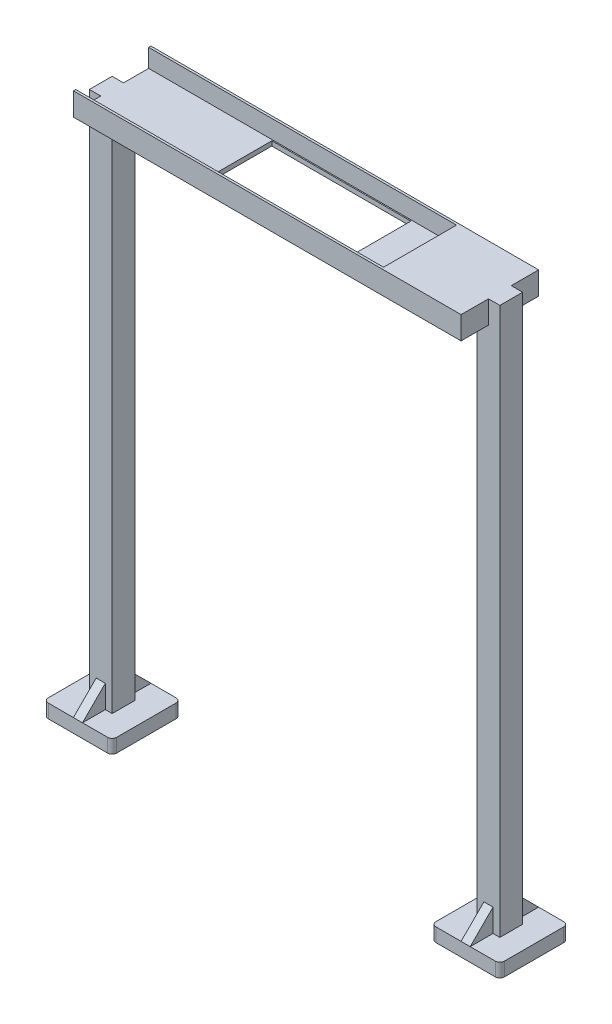
SolidWorks part; units mm, degrees
material "ABS"
ref_plane "Alzado" through (0, 0, 0) normal (0, 0, 1) x (1, 0, 0)
ref_plane "Planta" through (0, 0, 0) normal (0, 1, 0) x (1, 0, 0)
ref_plane "Vista lateral" through (0, 0, 0) normal (1, 0, 0) x (0, 0, -1)
sketch "Croquis1" plane through (0, 0, 0) normal (0, 1, 0) x (1, 0, 0)
  line L0 (42.5, 6.5) -> (42.5, -6.5) construction
  line L1 (-6.5, -7.5) -> (6.5, -7.5)
  line L2 (-7.5, -6.5) -> (-7.5, 6.5)
  line L3 (-6.5, 7.5) -> (6.5, 7.5)
  line L4 (7.5, -6.5) -> (7.5, 6.5)
  line L5 (-7.5, -7.5) -> (7.5, 7.5) construction
  line L6 (-7.5, 7.5) -> (7.5, -7.5) construction
  line L7 (92.5, 7.5) -> (77.5, -7.5) construction
  line L8 (92.5, -7.5) -> (77.5, 7.5) construction
  line L9 (77.5, -6.5) -> (77.5, 6.5)
  line L10 (91.5, 7.5) -> (78.5, 7.5)
  line L11 (92.5, -6.5) -> (92.5, 6.5)
  line L12 (91.5, -7.5) -> (78.5, -7.5)
  arc A0 (6.5, -7.5) -> (7.5, -6.5) centre (6.5, -6.5) ccw
  arc A1 (6.5, 7.5) -> (7.5, 6.5) centre (6.5, 6.5) cw
  arc A2 (-7.5, 6.5) -> (-6.5, 7.5) centre (-6.5, 6.5) cw
  arc A3 (-6.5, -7.5) -> (-7.5, -6.5) centre (-6.5, -6.5) cw
  arc A4 (91.5, -7.5) -> (92.5, -6.5) centre (91.5, -6.5) ccw
  arc A5 (92.5, 6.5) -> (91.5, 7.5) centre (91.5, 6.5) ccw
  arc A6 (78.5, 7.5) -> (77.5, 6.5) centre (78.5, 6.5) ccw
  arc A7 (78.5, -7.5) -> (77.5, -6.5) centre (78.5, -6.5) cw
  point P0 (0, 0)
  point P36 (85, 0)
  dimension "D3" = 1
  dimension "D1" = 15
  dimension "D2" = 15
  dimension "D4" = 35
extrude "Saliente-Extruir1" add sketch "Croquis1" along normal blind 3
sketch "Croquis2" plane through (0, 0, 0) normal (1, 0, 0) x (0, 0, -1)
  line L0 (0, 0) -> (0, 10.8965) construction
  line L1 (-7.5, 3) -> (-2.5, 8)
  line L2 (-2.5, 8) -> (-2.5, 3)
  line L3 (-6.5, 3) -> (6.5, 3) construction
  line L4 (-2.5, 3) -> (-7.5, 3)
  line L5 (2.5, 3) -> (7.5, 3)
  line L6 (2.5, 8) -> (2.5, 3)
  line L7 (7.5, 3) -> (2.5, 8)
  line L9 (0, 0) -> (0, 10.8965) construction
  dimension "D1" = 5
  dimension "D2" = 5
extrude "Saliente-Extruir2" add sketch "Croquis2" against normal blind 1 and the other way blind 1
sketch "Croquis3" plane through (0, 3, 0) normal (0, 1, 0) x (1, 0, 0)
  line L1 (2.5, -2.5) -> (-2.5, -2.5)
  line L2 (2.5, -2.5) -> (2.5, 2.5)
  line L3 (2.5, 2.5) -> (-2.5, 2.5)
  line L4 (-2.5, -2.5) -> (-2.5, 2.5)
  line L5 (2.5, -2.5) -> (-2.5, 2.5) construction
  line L6 (2.5, 2.5) -> (-2.5, -2.5) construction
  point P0 (0, 0)
  dimension "D1" = 5
  dimension "D2" = 5
extrude "Saliente-Extruir3" add sketch "Croquis3" along normal blind 120
sketch "Croquis4" plane through (0, 0, 0) normal (0, 1, 0) x (1, 0, 0)
  line L0 (7.5, 6.5) -> (7.5, -6.5) construction
  line L2 (47.5, 6.5) -> (47.5, -6.5) construction
  dimension "D1" = 40
ref_plane "Plano1" through (85, 0, 0) normal (1, 0, 0) x (0, 0, -1)
sketch "Croquis5" plane through (85, 0, 0) normal (1, 0, 0) x (0, 0, -1)
  line L0 (0, 0) -> (0, 12.552) construction
  line L1 (-7.5, 3) -> (-2.5, 8)
  line L2 (-2.5, 8) -> (-2.5, 3)
  line L3 (-2.5, 3) -> (-7.5, 3)
  line L4 (2.5, 8) -> (2.5, 3)
  line L5 (7.5, 3) -> (2.5, 8)
  line L6 (2.5, 3) -> (7.5, 3)
extrude "Saliente-Extruir4" add sketch "Croquis5" along normal blind 1 and the other way blind 1
sketch "Croquis7" plane through (0, 3, 0) normal (0, 1, 0) x (1, 0, 0)
  line L0 (85, -1.65) -> (85, 1.65) construction
  line L1 (82.5, -2.5) -> (87.5, -2.5)
  line L2 (82.5, -2.5) -> (82.5, 2.5)
  line L3 (82.5, 2.5) -> (87.5, 2.5)
  line L4 (87.5, -2.5) -> (87.5, 2.5)
  line L5 (82.5, -2.5) -> (87.5, 2.5) construction
  line L6 (82.5, 2.5) -> (87.5, -2.5) construction
  point P0 (85, 0)
  dimension "D1" = 5
  dimension "D2" = 5
extrude "Saliente-Extruir6" add sketch "Croquis7" along normal blind 120
ref_plane "Plano2" through (0, 118, 0) normal (0, 1, 0) x (1, 0, 0)
sketch "Croquis8" plane through (0, 118, 0) normal (0, 1, 0) x (1, 0, 0)
  line L0 (0, 0) -> (0, -8.5) construction
  line L3 (0, -8.5) -> (85, -8.5)
  line L4 (0, -8.5) -> (0, 8.5)
  line L5 (0, 8.5) -> (85, 8.5)
  line L6 (85, -8.5) -> (85, 8.5)
  line L7 (0, 0) -> (85, 0) construction
  line L13 (27.25, -7.75) -> (57.75, 7.75) construction
  point P2 (42.5, 0)
  dimension "D1" = 17
extrude "Saliente-Extruir7" add sketch "Croquis8" along normal blind 5
sketch "Croquis9" plane through (-2.5, 0, 0) normal (-1, 0, 0) x (0, 0, 1)
  line L0 (0, 123) -> (0, 118) construction
  line L1 (-2.5, 123) -> (2.5, 123) construction
  line L2 (9.35, 118) -> (-9.35, 118) construction
  line L3 (0, 118) -> (-2.5, 118) construction
  line L4 (-2.5, 123) -> (-2.5, 3) construction
  line L5 (-2.5, 118) -> (2.5672, 118) construction
  line L7 (-8, 119) -> (8, 119)
  line L8 (-8, 119) -> (-8, 123)
  line L9 (-8, 123) -> (8, 123)
  line L10 (8, 119) -> (8, 123)
  line L11 (-8, 119) -> (8, 123) construction
  line L12 (-8, 123) -> (8, 119) construction
  point P7 (0, 121)
  dimension "D1" = 1
  dimension "D2" = 4
  dimension "D3" = 16
extrude "Cortar-Extruir1" cut sketch "Croquis9" against normal blind 70
sketch "Croquis10" plane through (0, 118, 0) normal (0, -1, 0) x (1, 0, 0)
  line L0 (42.5, 8.5) -> (42.5, -8.5) construction
  line L1 (0, 8.5) -> (85, 8.5) construction
  line L2 (85, -8.5) -> (0, -8.5) construction
  line L4 (27.25, -7.75) -> (57.75, -7.75)
  line L5 (27.25, -7.75) -> (27.25, 7.75)
  line L6 (27.25, 7.75) -> (57.75, 7.75)
  line L7 (57.75, -7.75) -> (57.75, 7.75)
  line L8 (27.25, -7.75) -> (57.75, 7.75) construction
  line L9 (27.25, 7.75) -> (57.75, -7.75) construction
  point P6 (42.5, 0)
  dimension "D1" = 30.5
  dimension "D2" = 15.5
extrude "Cortar-Extruir2" cut sketch "Croquis10" against normal blind 2
